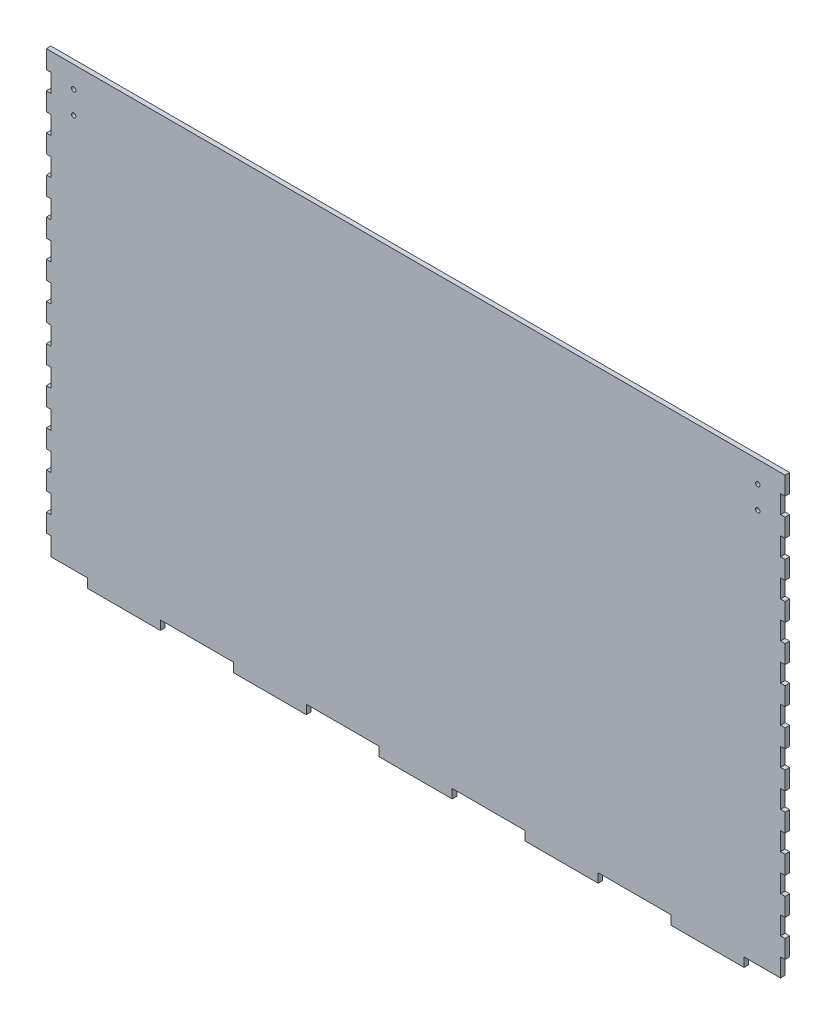
SolidWorks part; units mm, degrees
material "Acrylic (Medium-high impact)"
ref_plane "Front Plane" through (0, 0, 0) normal (0, 0, 1) x (1, 0, 0)
ref_plane "Top Plane" through (0, 0, 0) normal (0, 1, 0) x (1, 0, 0)
ref_plane "Right Plane" through (0, 0, 0) normal (1, 0, 0) x (0, 0, -1)
sketch "Sketch1" plane through (0, 0, 0) normal (0, 0, 1) x (1, 0, 0)
  line L0 (0, 0) -> (508, 0)
  line L1 (508, 0) -> (508, 304.8)
  line L2 (508, 304.8) -> (0, 304.8)
  line L3 (0, 304.8) -> (0, 0)
  line L4 (254, 304.8) -> (254, 0) construction
  line L5 (0, 304.8) -> (-3.175, 304.8)
  line L6 (-3.175, 304.8) -> (-3.175, 292.1)
  line L7 (-3.175, 292.1) -> (0, 292.1)
  line L8 (25.4, 0) -> (25.4, -6.35)
  line L9 (25.4, -6.35) -> (76.2, -6.35)
  line L10 (76.2, -6.35) -> (76.2, 0)
  line L13 (0, 279.4) -> (-3.175, 279.4)
  line L14 (-3.175, 279.4) -> (-3.175, 266.7)
  line L15 (-3.175, 266.7) -> (0, 266.7)
  line L17 (0, 254) -> (-3.175, 254)
  line L18 (-3.175, 254) -> (-3.175, 241.3)
  line L19 (-3.175, 241.3) -> (0, 241.3)
  line L21 (0, 228.6) -> (-3.175, 228.6)
  line L22 (-3.175, 228.6) -> (-3.175, 215.9)
  line L23 (-3.175, 215.9) -> (0, 215.9)
  line L25 (0, 203.2) -> (-3.175, 203.2)
  line L26 (-3.175, 203.2) -> (-3.175, 190.5)
  line L27 (-3.175, 190.5) -> (0, 190.5)
  line L29 (0, 177.8) -> (-3.175, 177.8)
  line L30 (-3.175, 177.8) -> (-3.175, 165.1)
  line L31 (-3.175, 165.1) -> (0, 165.1)
  line L33 (0, 152.4) -> (-3.175, 152.4)
  line L34 (-3.175, 152.4) -> (-3.175, 139.7)
  line L35 (-3.175, 139.7) -> (0, 139.7)
  line L37 (0, 127) -> (-3.175, 127)
  line L38 (-3.175, 127) -> (-3.175, 114.3)
  line L39 (-3.175, 114.3) -> (0, 114.3)
  line L41 (0, 101.6) -> (-3.175, 101.6)
  line L42 (-3.175, 101.6) -> (-3.175, 88.9)
  line L43 (-3.175, 88.9) -> (0, 88.9)
  line L45 (0, 76.2) -> (-3.175, 76.2)
  line L46 (-3.175, 76.2) -> (-3.175, 63.5)
  line L47 (-3.175, 63.5) -> (0, 63.5)
  line L49 (0, 50.8) -> (-3.175, 50.8)
  line L50 (-3.175, 50.8) -> (-3.175, 38.1)
  line L51 (-3.175, 38.1) -> (0, 38.1)
  line L53 (0, 25.4) -> (-3.175, 25.4)
  line L54 (-3.175, 25.4) -> (-3.175, 12.7)
  line L55 (-3.175, 12.7) -> (0, 12.7)
  line L57 (0, 304.8) -> (0, 279.4) construction
  line L59 (127, 0) -> (127, -6.35)
  line L60 (127, -6.35) -> (177.8, -6.35)
  line L61 (177.8, -6.35) -> (177.8, 0)
  line L63 (228.6, 0) -> (228.6, -6.35)
  line L64 (228.6, -6.35) -> (279.4, -6.35)
  line L65 (279.4, -6.35) -> (279.4, 0)
  line L67 (330.2, 0) -> (330.2, -6.35)
  line L68 (330.2, -6.35) -> (381, -6.35)
  line L69 (381, -6.35) -> (381, 0)
  line L70 (76.2, 0) -> (177.8, 0) construction
  line L72 (431.8, 0) -> (431.8, -6.35)
  line L73 (431.8, -6.35) -> (482.6, -6.35)
  line L74 (482.6, -6.35) -> (482.6, 0)
  line L76 (511.175, 12.7) -> (508, 12.7)
  line L77 (511.175, 25.4) -> (511.175, 12.7)
  line L78 (508, 25.4) -> (511.175, 25.4)
  line L80 (511.175, 38.1) -> (508, 38.1)
  line L81 (511.175, 50.8) -> (511.175, 38.1)
  line L82 (508, 50.8) -> (511.175, 50.8)
  line L84 (511.175, 63.5) -> (508, 63.5)
  line L85 (511.175, 76.2) -> (511.175, 63.5)
  line L86 (508, 76.2) -> (511.175, 76.2)
  line L88 (511.175, 88.9) -> (508, 88.9)
  line L89 (511.175, 101.6) -> (511.175, 88.9)
  line L90 (508, 101.6) -> (511.175, 101.6)
  line L92 (511.175, 114.3) -> (508, 114.3)
  line L93 (511.175, 127) -> (511.175, 114.3)
  line L94 (508, 127) -> (511.175, 127)
  line L96 (511.175, 139.7) -> (508, 139.7)
  line L97 (511.175, 152.4) -> (511.175, 139.7)
  line L98 (508, 152.4) -> (511.175, 152.4)
  line L100 (511.175, 165.1) -> (508, 165.1)
  line L101 (511.175, 177.8) -> (511.175, 165.1)
  line L102 (508, 177.8) -> (511.175, 177.8)
  line L104 (511.175, 190.5) -> (508, 190.5)
  line L105 (511.175, 203.2) -> (511.175, 190.5)
  line L106 (508, 203.2) -> (511.175, 203.2)
  line L108 (511.175, 215.9) -> (508, 215.9)
  line L109 (511.175, 228.6) -> (511.175, 215.9)
  line L110 (508, 228.6) -> (511.175, 228.6)
  line L112 (511.175, 241.3) -> (508, 241.3)
  line L113 (511.175, 254) -> (511.175, 241.3)
  line L114 (508, 254) -> (511.175, 254)
  line L116 (511.175, 266.7) -> (508, 266.7)
  line L117 (511.175, 279.4) -> (511.175, 266.7)
  line L118 (508, 279.4) -> (511.175, 279.4)
  line L120 (511.175, 292.1) -> (508, 292.1)
  line L121 (511.175, 304.8) -> (511.175, 292.1)
  line L122 (508, 304.8) -> (511.175, 304.8)
  dimension "D1" = 508
  dimension "D2" = 304.8
  dimension "D3" = 3.175
  dimension "D4" = 12.7
  dimension "D5" = 6.35
  dimension "D6" = 50.8
  dimension "D7" = 25.4
  dimension "D9" = 25.4
  dimension "D11" = 101.6
  dimension "D8" = 12
  dimension "D10" = 5
extrude "Boss-Extrude1" add sketch "Sketch1" along normal blind 3.175 contours L2 L3 L0 L1 | L9 L10 L0 L8 | L60 L61 L0 L59 | L64 L65 L0 L63 | L68 L69 L0 L67 | L73 L74 L0 L72 | L54 L55 L3 L53 | L50 L51 L3 L49 | L46 L47 L3 L45 | L42 L43 L3 L41 | L38 L39 L3 L37 | L34 L35 L3 L33 | L30 L31 L3 L29 | L26 L27 L3 L25 | L22 L23 L3 L21 | L18 L19 L3 L17 | L14 L15 L3 L13 | L6 L7 L3 L5 | L78 L1 L76 L77 | L82 L1 L80 L81 | L86 L1 L84 L85 | L90 L1 L88 L89 | L98 L1 L96 L97 | L94 L1 L92 L93 | L102 L1 L100 L101 | L106 L1 L104 L105 | L110 L1 L108 L109 | L114 L1 L112 L113 | L118 L1 L116 L117 | L122 L1 L120 L121
sketch "Sketch2" plane through (0, 0, 3.175) normal (0, 0, 1) x (1, 0, 0)
  line L1 (511.175, 304.8) -> (-3.175, 304.8) construction
  line L2 (254, 304.8) -> (254, -6.35) construction
  line L3 (228.6, -6.35) -> (279.4, -6.35) construction
  line L4 (-3.175, 304.8) -> (-3.175, 292.1) construction
  circle A0 centre (15.875, 289.8) radius 1.5
  circle A1 centre (15.875, 274.05) radius 1.5
  circle A2 centre (492.125, 289.8) radius 1.5
  circle A3 centre (492.125, 274.05) radius 1.5
  dimension "D1" = 3
  dimension "D2" = 3
  dimension "D3" = 19.05
  dimension "D4" = 15.75
  dimension "D5" = 15
extrude "Cut-Extrude1" cut sketch "Sketch2" against normal up to surface (3.175 mm away) up to face at (254, 125.5767, 0)
equation "\"wall_thickness\"= 0.125in"
equation "\"base_thickness\"= 0.25in"
equation "\"D3@Sketch1\"=\"wall_thickness\""
equation "\"D5@Sketch1\"=\"base_thickness\""
equation "\"D1@Boss-Extrude1\"=\"wall_thickness\""
